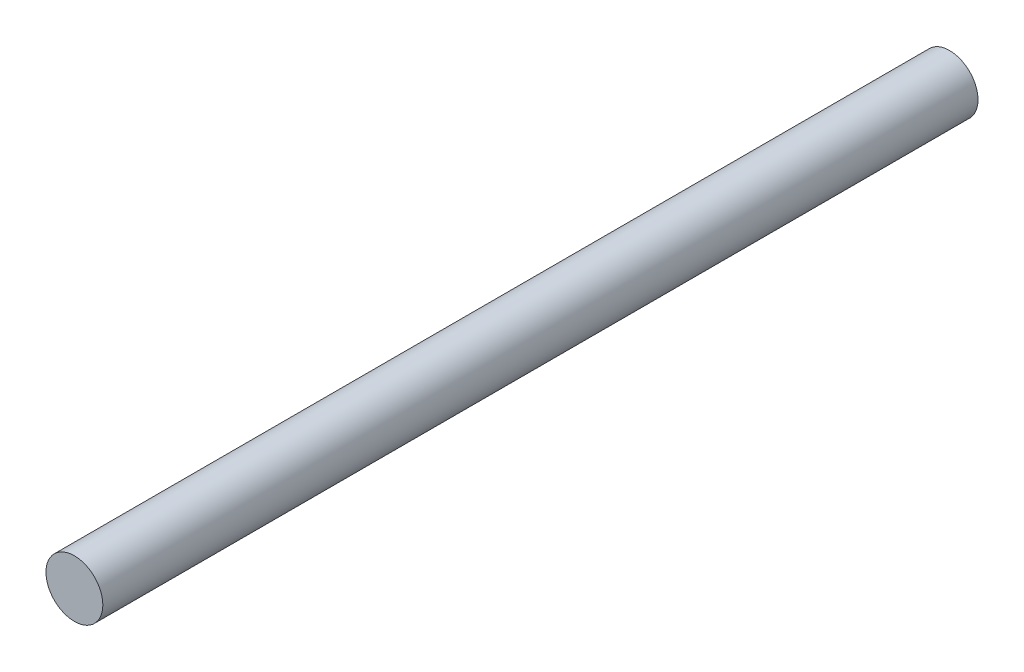
SolidWorks part; units mm, degrees
ref_plane "Front Plane" through (0, 0, 0) normal (0, 0, 1) x (1, 0, 0)
ref_plane "Top Plane" through (0, 0, 0) normal (0, 1, 0) x (1, 0, 0)
ref_plane "Right Plane" through (0, 0, 0) normal (1, 0, 0) x (0, 0, -1)
sketch "Sketch1" plane through (0, 0, 0) normal (0, 0, 1) x (1, 0, 0)
  circle A0 centre (0, 0) radius 13
  dimension "D1" = 26
extrude "Boss-Extrude1" add sketch "Sketch1" along normal blind 400
